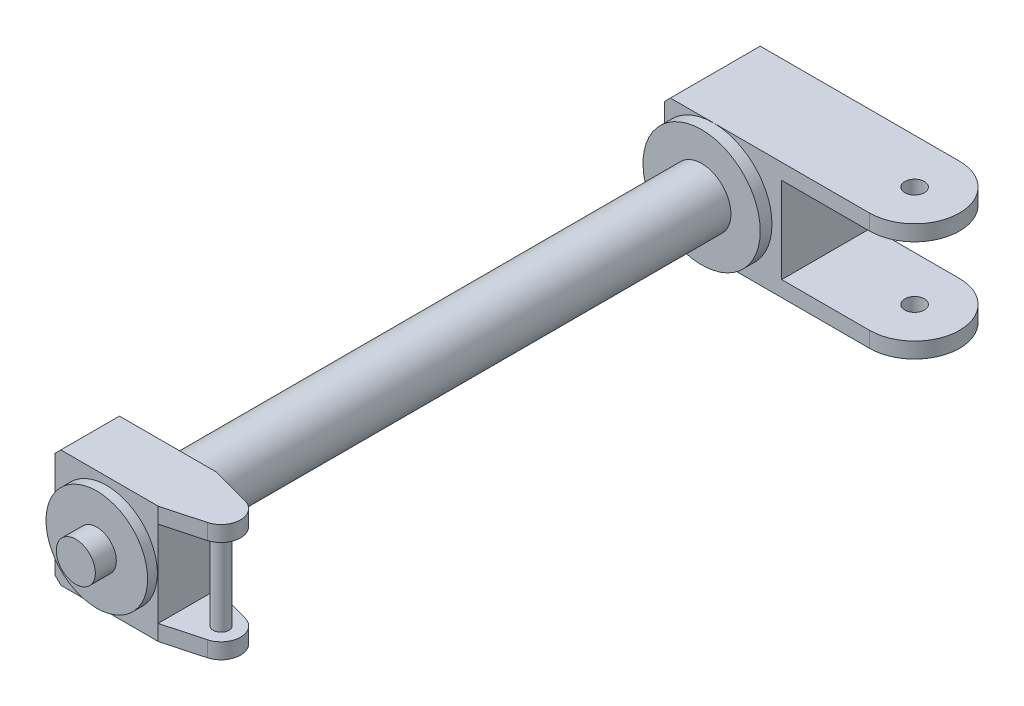
SolidWorks part; units mm, degrees
ref_plane "Alzado" through (0, 0, 0) normal (0, 0, 1) x (1, 0, 0)
ref_plane "Planta" through (0, 0, 0) normal (0, 1, 0) x (1, 0, 0)
ref_plane "Vista lateral" through (0, 0, 0) normal (1, 0, 0) x (0, 0, -1)
other "Centro de masa"
sketch "Croquis2" plane through (0, 0, 0) normal (0, 1, 0) x (1, 0, 0)
  line L0 (0, 0) -> (151.2871, 0) construction
  line L1 (-25, -23) -> (-25, 23)
  line L2 (-25, -23) -> (80, -23)
  line L4 (-25, 23) -> (80, 23)
  arc A0 (80, -23) -> (80, 23) centre (80, 0) ccw
  dimension "D2" = 105
  dimension "D1" = 46
  dimension "D3" = 25
extrude "Saliente-Extruir1" add sketch "Croquis2" along normal blind 60
sketch "Croquis3" plane through (0, 0, 0) normal (0, 1, 0) x (1, 0, 0)
  circle A0 centre (80, 0) radius 21
extrude "Saliente-Extruir2" [suppressed] add sketch "Croquis3" against normal blind 5.5
sketch "Croquis4" [suppressed] plane through (0, 60, 0) normal (0, -1, 0) x (1, 0, 0)
  circle A0 centre (80, 0) radius 21 construction
  circle A1 centre (80, 0) radius 21
extrude "Saliente-Extruir3" [suppressed] add sketch "Croquis4" against normal blind 5.5
sketch "Croquis5" plane through (0, 0, 23) normal (0, 0, 1) x (1, 0, 0)
  line L0 (103, 0) -> (103, 60) construction
  line L1 (35, 52) -> (103, 52)
  line L2 (35, 52) -> (35, 8)
  line L3 (35, 8) -> (103, 8)
  line L4 (103, 52) -> (103, 8)
  line L5 (-25, 60) -> (-25, 0) construction
  line L6 (-25, 60) -> (80, 60) construction
  line L7 (-25, 30) -> (160.4912, 30) construction
  dimension "D1" = 60
  dimension "D2" = 8
extrude "Cortar-Extruir1" cut sketch "Croquis5" against normal through all
chamfer "Chaflán1" distance 3 angle 45 2 edges at (-25, 60, 0) (-25, 0, 0)
sketch "Croquis6" plane through (0, 0, 23) normal (0, 0, 1) x (1, 0, 0)
  line L0 (35, 30) -> (-17.1626, 30) construction
  line L1 (35, 52) -> (35, 8) construction
  line L2 (-25, 57) -> (-25, 3) construction
  circle A0 centre (0, 30) radius 30
  dimension "D1" = 25
  dimension "D2" = 60
extrude "Saliente-Extruir4" add sketch "Croquis6" along normal blind 6
sketch "Croquis7" plane through (0, 0, 29) normal (0, 0, 1) x (1, 0, 0)
  circle A0 centre (0, 30) radius 15
  dimension "D1" = 30
extrude "Saliente-Extruir5" add sketch "Croquis7" along normal blind 276
sketch "Croquis8" plane through (0, 0, 305) normal (0, 0, 1) x (1, 0, 0)
  line L1 (-22, 60) -> (-25, 57) construction
  line L4 (-25, 3) -> (-22, 0) construction
  line L6 (-22, 60) -> (55, 60)
  line L7 (-22, 60) -> (-25, 57)
  line L8 (-25, 57) -> (-25, 3)
  line L9 (0, 60) -> (80, 60) construction
  line L10 (-25, 3) -> (-22, 0)
  line L11 (55, 60) -> (55, 0)
  line L12 (0, 0) -> (80, 0) construction
  line L13 (55, 0) -> (-22, 0)
  dimension "D1" = 80
extrude "Saliente-Extruir6" add sketch "Croquis8" along normal blind 30
sketch "Croquis9" plane through (0, 0, 335) normal (0, 0, 1) x (1, 0, 0)
  line L0 (55, 30) -> (-25, 30) construction
  line L1 (55, 0) -> (55, 60) construction
  line L2 (-25, 57) -> (-25, 3) construction
  line L3 (80, 52) -> (35, 52) construction
  line L4 (55, 52) -> (27.8, 52)
  line L5 (55, 52) -> (55, 8)
  line L6 (55, 8) -> (27.8, 8)
  line L7 (27.8, 52) -> (27.8, 8)
  line L8 (35, 8) -> (80, 8) construction
  dimension "D1" = 52.8
extrude "Cortar-Extruir2" cut sketch "Croquis9" against normal up to next
sketch "Croquis10" plane through (0, 0, 0) normal (0, -1, 0) x (1, 0, 0)
  line L0 (55, 320) -> (-22, 320) construction
  line L1 (55, 335) -> (55, 305) construction
  line L2 (-22, 335) -> (-22, 305) construction
  line L3 (27.8, 305) -> (27.8, 335) construction
  line L4 (27.8, 305) -> (27.8, 335) construction
  line L5 (27.8, 335) -> (47.6057, 329.6545)
  line L6 (27.8, 305) -> (55, 305)
  line L7 (47.6057, 310.3455) -> (27.8, 305)
  line L8 (55, 305) -> (55, 335)
  line L9 (55, 335) -> (27.8, 335)
  arc A0 (47.6057, 310.3455) -> (47.6057, 329.6545) centre (45, 320) ccw
  line M1 (-22, 305) -> (55, 305)
  line M2 (55, 305) -> (55, 335)
  line M3 (55, 335) -> (-22, 335)
  dimension "D1" = 20
extrude "Cortar-Extruir3" cut sketch "Croquis10" against normal blind 60 contours A0 L8 L5 M3 | A0 L7 M1 M2
sketch "Croquis11" plane through (0, 52, 0) normal (0, -1, 0) x (1, 0, 0)
  circle A0 centre (45, 320) radius 4
extrude "Saliente-Extruir7" add sketch "Croquis11" along normal up to next
sketch "Croquis13" plane through (0, 0, 335) normal (0, 0, 1) x (1, 0, 0)
  line L1 (-25, 30) -> (27.8, 30) construction
  line L3 (-25, 57) -> (-25, 3) construction
  line L4 (27.8, 52) -> (27.8, 8) construction
  circle A0 centre (1.4, 30) radius 26
  dimension "D1" = 52
extrude "Saliente-Extruir8" add sketch "Croquis13" along normal blind 5
sketch "Croquis14" plane through (0, 0, 340) normal (0, 0, 1) x (1, 0, 0)
  circle A0 centre (1.4, 30) radius 10
  dimension "D1" = 20
extrude "Saliente-Extruir9" add sketch "Croquis14" along normal blind 10.75
sketch "Croquis15" plane through (0, 0, 0) normal (0, -1, 0) x (1, 0, 0)
  circle A0 centre (80, 0) radius 5
  dimension "D1" = 10
extrude "Cortar-Extruir4" cut sketch "Croquis15" against normal through all
